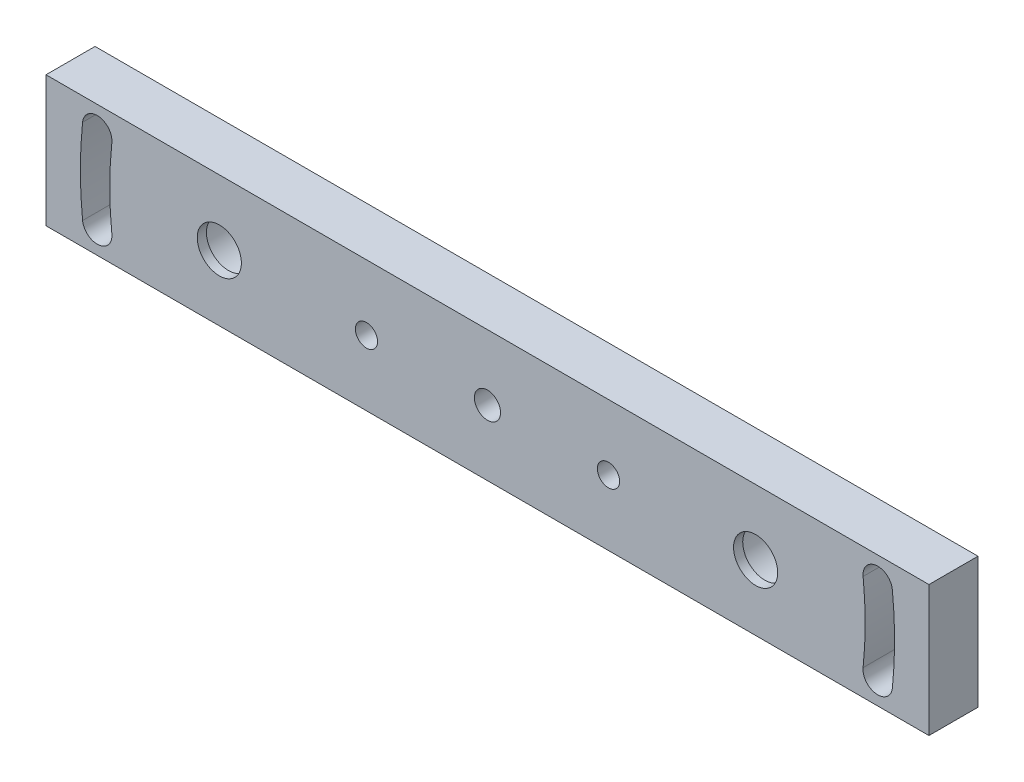
SolidWorks part; units mm, degrees
material "6061"
ref_plane "前视" through (0, 0, 0) normal (0, 0, 1) x (1, 0, 0)
ref_plane "上视" through (0, 0, 0) normal (0, 1, 0) x (1, 0, 0)
ref_plane "右视" through (0, 0, 0) normal (1, 0, 0) x (0, 0, -1)
sketch "草图1" plane through (0, 0, 0) normal (0, 0, 1) x (1, 0, 0)
  line L1 (-135, -20) -> (135, -20)
  line L2 (-135, -20) -> (-135, 20)
  line L3 (-135, 20) -> (135, 20)
  line L4 (135, -20) -> (135, 20)
  line L5 (-135, -20) -> (135, 20) construction
  line L6 (-135, 20) -> (135, -20) construction
  point P0 (0, 0)
  dimension "D1" = 270
  dimension "D2" = 40
extrude "凸台-拉伸1" add sketch "草图1" along normal blind 15
hole_wizard "打孔尺寸根据内六角圆柱头螺钉的类型1" positions "草图3" profile "草图2" counterbore size "M12" standard "Gb" end condition through all
sketch "草图3" plane through (0, 0, 0) normal (0, 0, -1) x (-1, 0, 0)
  line L0 (-135, 0) -> (0, 0) construction
  line L1 (-135, -20) -> (-135, 20) construction
  line L2 (0, 0) -> (0, 20) construction
  line L3 (-135, 20) -> (135, 20) construction
  point P0 (-82, 0)
  point P14 (82, 0)
  dimension "D1" = 164
sketch "草图2" plane through (82, 0, 0) normal (1, 0, 0) x (0, 1, 0)
  line L0 (0, 0) -> (0, 15)
  line L1 (0, 15) -> (6.75, 15)
  line L3 (6.75, 15) -> (6.75, 12.2)
  line L4 (6.75, 12.2) -> (10, 12.2)
  line L5 (10, 12.2) -> (10, 0)
  line L7 (10, 0) -> (0, 0)
  line L11 (0, -6.35) -> (0, 107.95) construction
  dimension "通孔孔直径" = 13.5
  dimension "通孔孔深度" = 15
  dimension "柱形沉头孔直径" = 20
  dimension "柱形沉头孔深度" = 12.2
sketch "草图4" plane through (0, 0, 15) normal (0, 0, 1) x (1, 0, 0)
  line L0 (-135, 0) -> (0, 0) construction
  line L1 (-135, 20) -> (-135, -20) construction
  line L2 (0, 0) -> (0, 20) construction
  line L3 (135, 20) -> (-135, 20) construction
  line L4 (0, 0) -> (123.818, 13.0138) construction
  line L5 (0, 0) -> (123.818, -13.0138) construction
  arc A0 (114.8673, -12.073) -> (114.8673, 12.073) centre (0, 0) ccw
  arc A1 (123.818, -13.0138) -> (123.818, 13.0138) centre (0, 0) ccw
  circle A2 centre (0, 0) radius 120 construction
  arc A3 (123.818, 13.0138) -> (114.8673, 12.073) centre (119.3426, 12.5434) ccw
  arc A4 (114.8673, -12.073) -> (123.818, -13.0138) centre (119.3426, -12.5434) ccw
  arc A5 (-114.8673, -12.073) -> (-123.818, -13.0138) centre (-119.3426, -12.5434) cw
  arc A6 (-123.818, 13.0138) -> (-114.8673, 12.073) centre (-119.3426, 12.5434) cw
  arc A7 (-123.818, -13.0138) -> (-123.818, 13.0138) centre (0, 0) cw
  arc A8 (-114.8673, -12.073) -> (-114.8673, 12.073) centre (0, 0) cw
  dimension "D1" = 240
  dimension "D2" = 9
  dimension "D3" = 12
extrude "切除-拉伸1" cut sketch "草图4" against normal through all
hole_wizard "M8 螺纹孔1" positions "草图6" profile "草图5" tap size "M8" standard "Gb" end condition through all
sketch "草图6" plane through (0, 0, 15) normal (0, 0, 1) x (1, 0, 0)
  line L0 (-82, 0) -> (0, 0) construction
  line L1 (0, 0) -> (0, 20) construction
  line L2 (135, 20) -> (-135, 20) construction
  circle A0 centre (-82, 0) radius 6.75 construction
  point P0 (-37, 0)
  point P13 (37, 0)
  dimension "D1" = 45
sketch "草图5" plane through (-37, 0, 15) normal (1, 0, 0) x (0, -1, 0)
  line L0 (0, 0) -> (0, 15)
  line L1 (0, 15) -> (3.4, 15)
  line L2 (3.4, 15) -> (3.4, 0)
  line L5 (3.4, 0) -> (0, 0)
  line L11 (0, -6.35) -> (0, 107.95) construction
  dimension "通孔螺纹孔钻头直径" = 6.8
  dimension "通孔螺纹孔钻头深度" = 15
cosmetic thread "孔螺蚊线1" parameters "D2"=8
cosmetic thread "孔螺蚊线2" parameters "D2"=8
hole_wizard "孔1" positions "草图9" profile "草图7" legacy end condition through all
sketch "草图9" plane through (0, 0, 0) normal (0, 0, -1) x (-1, 0, 0)
  point P0 (0, 0)
sketch "草图7" plane through (0, 0, 0) normal (1, 0, 0) x (0, 1, 0)
  line L0 (0, 0) -> (0, 15)
  line L1 (0, 15) -> (4, 15)
  line L2 (4, 15) -> (4, 0)
  line L3 (4, 0) -> (0, 0)
  line L4 (0, 110) -> (0, -10) construction
  dimension "直径" = 8
  dimension "深度" = 15
